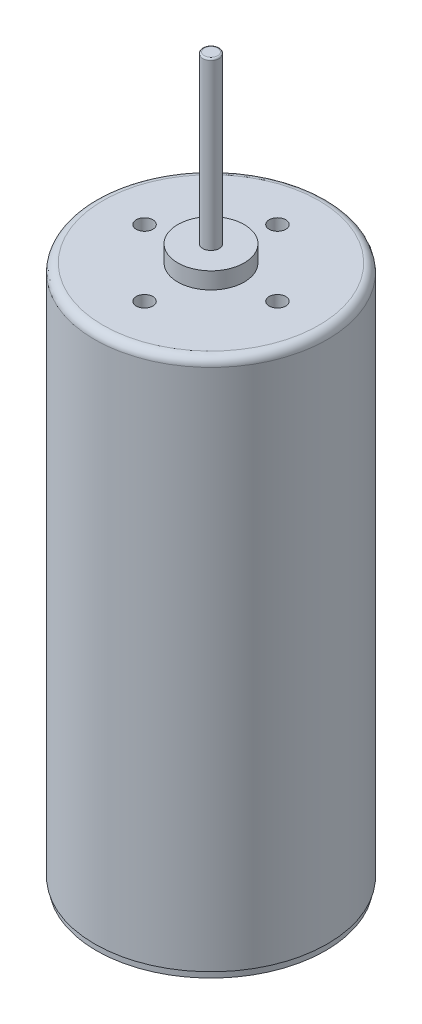
SolidWorks part; units mm, degrees
ref_plane "Plano frontal" through (0, 0, 0) normal (0, 0, 1) x (1, 0, 0)
ref_plane "Plano superior" through (0, 0, 0) normal (0, 1, 0) x (1, 0, 0)
ref_plane "Plano direito" through (0, 0, 0) normal (1, 0, 0) x (0, 0, -1)
sketch "Esboço1" plane through (0, 0, 0) normal (0, 1, 0) x (1, 0, 0)
  circle A0 centre (0, 0) radius 3.5
  dimension "D1" = 7
extrude "Ressalto-extrusão1" add sketch "Esboço1" along normal blind 16
sketch "Esboço2" plane through (0, 0, 0) normal (0, -1, 0) x (1, 0, 0)
  circle A0 centre (0, 0) radius 3.45
  dimension "D1" = 6.9
extrude "Ressalto-extrusão2" add sketch "Esboço2" along normal blind 0.2
sketch "Esboço3" plane through (0, -0.2, 0) normal (0, -1, 0) x (1, 0, 0)
  circle A0 centre (-2.5, 0) radius 0.375
  circle A1 centre (2.5, 0) radius 0.375
  dimension "D1" = 2.5
  dimension "D2" = 2.5
  dimension "D3" = 0.75
  dimension "D4" = 0.75
extrude "Corte-extrusão1" cut sketch "Esboço3" against normal blind 0.5
sketch "Esboço4" plane through (0, 16, 0) normal (0, 1, 0) x (1, 0, 0)
  circle A0 centre (0, 0) radius 1
  dimension "D1" = 2
extrude "Ressalto-extrusão3" add sketch "Esboço4" along normal blind 0.5
sketch "Esboço5" plane through (0, 16.5, 0) normal (0, 1, 0) x (1, 0, 0)
  circle A0 centre (0, 0) radius 0.25
  dimension "D1" = 0.5
extrude "Ressalto-extrusão4" add sketch "Esboço5" along normal blind 5
fillet "Filete1" radius 0.25 1 edges at (0, 16, 3.5)
fillet "Filete2" radius 0.05 1 edges at (0, 21.5, 0.25)
sketch "Esboço6" plane through (0, 16, 0) normal (0, 1, 0) x (1, 0, 0)
  circle A0 centre (0, 2) radius 0.25
  circle A1 centre (2, 0) radius 0.25
  circle A2 centre (0, -2) radius 0.25
  circle A3 centre (-2, 0) radius 0.25
  point P12 (0, 0)
  dimension "D1" = 0.5
  dimension "D2" = 2
  dimension "D3" = 4
extrude "Corte-extrusão2" cut sketch "Esboço6" against normal blind 1
